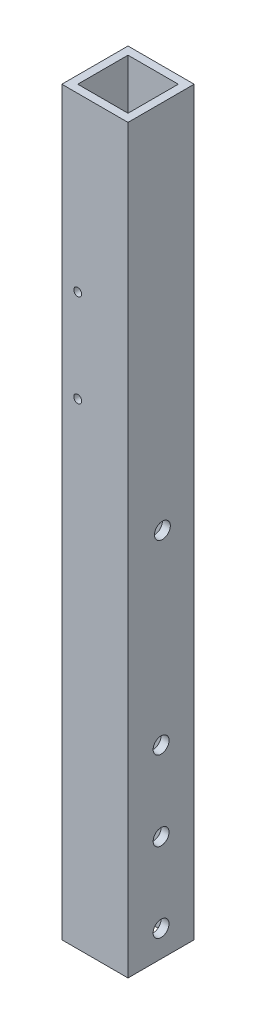
SolidWorks part; units mm, degrees
ref_plane "前视基准面" through (0, 0, 0) normal (0, 0, 1) x (1, 0, 0)
ref_plane "上视基准面" through (0, 0, 0) normal (0, 1, 0) x (1, 0, 0)
ref_plane "右视基准面" through (0, 0, 0) normal (1, 0, 0) x (0, 0, -1)
other "Configuration Table"
sketch "草图1" plane through (0, 0, 0) normal (0, 1, 0) x (1, 0, 0)
  line L1 (0, 0) -> (25, 0)
  line L2 (0, 0) -> (0, 25)
  line L3 (0, 25) -> (25, 25)
  line L4 (25, 0) -> (25, 25)
  line L5 (3, 3) -> (22, 3)
  line L6 (3, 3) -> (3, 22)
  line L7 (3, 22) -> (22, 22)
  line L8 (22, 3) -> (22, 22)
  dimension "D1" = 25
  dimension "D2" = 25
  dimension "D3" = 3
  dimension "D4" = 3
  dimension "D5" = 3
  dimension "D6" = 3
extrude "凸台-拉伸1" add sketch "草图1" along normal blind 280
sketch "草图2" plane through (0, 0, 0) normal (1, 0, 0) x (0, 0, -1)
  line L0 (12.5, -31.3312) -> (12.5, 287.2487) construction
  line L1 (12.5, 10) -> (12.5, 40) construction
  line L2 (25, 280) -> (25, 0) construction
  line L3 (0, 0) -> (25, 0) construction
  circle A0 centre (12.5, 10) radius 3
  circle A2 centre (12.5, 40) radius 3
  circle A3 centre (12.5, 70) radius 3
  circle A4 centre (13, 140) radius 3
  dimension "D2" = 6
  dimension "D3" = 3
  dimension "D6" = 6
  dimension "D1" = 12.5
  dimension "D4" = 10
  dimension "D5" = 30
  dimension "D7" = 12
  dimension "D8" = 140
extrude "切除-拉伸1" cut sketch "草图2" along normal through all
sketch "草图3" plane through (0, 0, 0) normal (0, 0, 1) x (1, 0, 0)
  line L0 (6, -7.4812) -> (6, 258.86) construction
  line L1 (6, 180) -> (6, 215) construction
  circle A0 centre (6, 180) radius 1.5
  circle A1 centre (6, 215) radius 1.5
  dimension "D2" = 3
  dimension "D1" = 6
  dimension "D4" = 180
  dimension "D5" = 35
  dimension "D3" = 2
extrude "切除-拉伸2" cut sketch "草图3" against normal through all both
